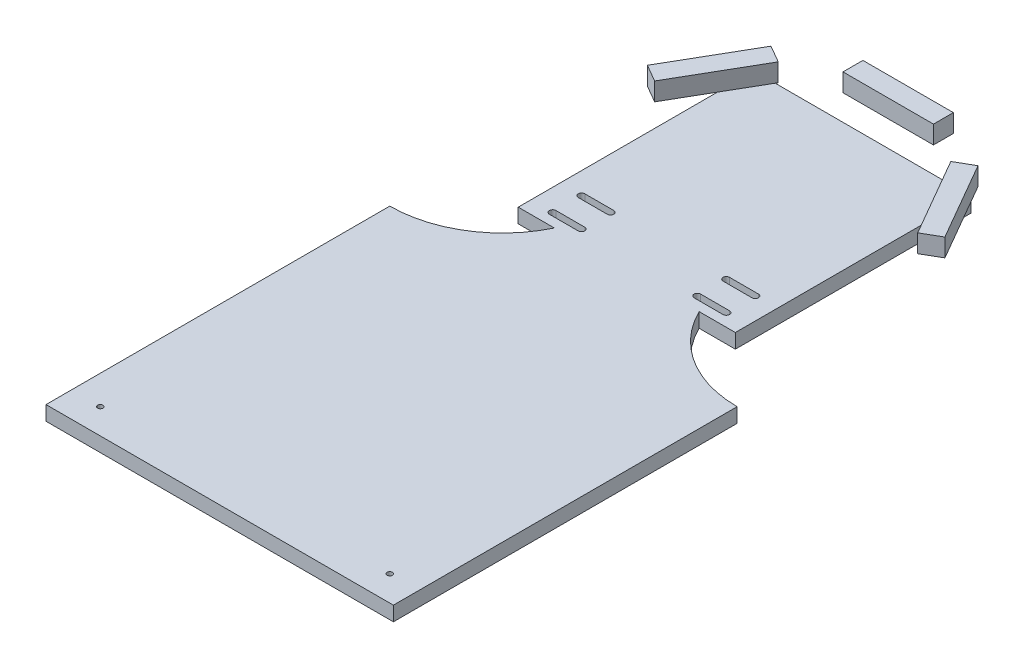
SolidWorks part; units mm, degrees
ref_plane "前视基准面" through (0, 0, 0) normal (0, 0, 1) x (1, 0, 0)
ref_plane "上视基准面" through (0, 0, 0) normal (0, 1, 0) x (1, 0, 0)
ref_plane "右视基准面" through (0, 0, 0) normal (1, 0, 0) x (0, 0, -1)
other "Configuration Table"
sketch "草图1" plane through (0, 0, 0) normal (0, 1, 0) x (1, 0, 0)
  line L1 (-60, 15) -> (60, 15) construction
  line L2 (-60, 15) -> (-60, -15)
  line L3 (-60, -15) -> (-40, -15)
  line L4 (60, 15) -> (60, -15)
  line L5 (-60, 15) -> (60, -15) construction
  line L6 (-60, -15) -> (60, 15) construction
  line L14 (-48, 8) -> (-32, 8) construction
  line L15 (-48, 9.8) -> (-32, 9.8)
  line L16 (-48, 6.2) -> (-32, 6.2)
  line L17 (-60, 0) -> (0, 0) construction
  line L18 (-48, -8) -> (-32, -8) construction
  line L19 (-48, -9.8) -> (-32, -9.8)
  line L20 (-48, -6.2) -> (-32, -6.2)
  line L21 (0, 15) -> (0, 0) construction
  line L22 (48, 8) -> (32, 8) construction
  line L23 (48, 9.8) -> (32, 9.8)
  line L24 (48, 6.2) -> (32, 6.2)
  line L25 (48, -8) -> (32, -8) construction
  line L26 (48, -9.8) -> (32, -9.8)
  line L27 (48, -6.2) -> (32, -6.2)
  line L28 (40, -15) -> (60, -15)
  line L31 (-40, -240) -> (40, -240)
  line L33 (40, -240) -> (96, -240)
  line L36 (-40, -240) -> (-96, -240)
  line L37 (-96, -50) -> (-96, -240)
  line L38 (96, -50) -> (96, -240)
  line L41 (60, 15) -> (-60, 15) construction
  line L42 (60, 15) -> (60, 115.3405)
  line L43 (60, 115.3405) -> (-60, 115.3405)
  line L44 (-60, 15) -> (-60, 115.3405)
  arc A4 (-48, 9.8) -> (-48, 6.2) centre (-48, 8) ccw
  arc A5 (-32, 6.2) -> (-32, 9.8) centre (-32, 8) ccw
  arc A6 (-48, -9.8) -> (-48, -6.2) centre (-48, -8) cw
  arc A7 (-32, -6.2) -> (-32, -9.8) centre (-32, -8) cw
  arc A8 (48, 9.8) -> (48, 6.2) centre (48, 8) cw
  arc A9 (32, 6.2) -> (32, 9.8) centre (32, 8) cw
  arc A10 (48, -9.8) -> (48, -6.2) centre (48, -8) ccw
  arc A11 (32, -6.2) -> (32, -9.8) centre (32, -8) ccw
  arc A12 (-96, -50) -> (-40, -15) centre (-96, 12.3) ccw
  arc A13 (96, -50) -> (40, -15) centre (96, 12.3) cw
  point P0 (0, 0)
  point P10 (40, 8)
  point P17 (40, -8)
  point P24 (-40, 8)
  point P33 (-40, -8)
  dimension "D5" = 8
  dimension "D1" = 30
  dimension "D2" = 120
  dimension "D3" = 3.6
  dimension "D4" = 16
  dimension "D6" = 40
  dimension "D8" = 80
  dimension "D9" = 240
  dimension "D11" = 190
extrude "凸台-拉伸1" add sketch "草图1" against normal blind 8
sketch "草图2" plane through (0, 0, 0) normal (0, 1, 0) x (1, 0, 0)
  line L0 (-82.215, -78.5994) -> (-57.215, -121.9006) construction
  line L1 (-96, -240) -> (96, -240) construction
  line L2 (0, -240) -> (0, -60) construction
  line L3 (-72.6888, -73.0994) -> (-47.6888, -116.4006) construction
  line L4 (-72.6888, -73.0994) -> (-82.215, -78.5994) construction
  line L5 (-25, -129.5) -> (25, -129.5) construction
  line L6 (-25, -129.5) -> (-25, -140.5) construction
  line L7 (-25, -140.5) -> (25, -140.5) construction
  line L8 (25, -129.5) -> (25, -140.5) construction
  line L9 (-25, -129.5) -> (25, -140.5) construction
  line L10 (-25, -140.5) -> (25, -129.5) construction
  line L11 (-47.6888, -116.4006) -> (-57.215, -121.9006) construction
  line L12 (47.6888, -116.4006) -> (72.6888, -73.0994) construction
  line L13 (47.6888, -116.4006) -> (57.215, -121.9006) construction
  line L14 (57.215, -121.9006) -> (82.215, -78.5994) construction
  line L15 (72.6888, -73.0994) -> (82.215, -78.5994) construction
  line L16 (-35.7665, 0) -> (35.7686, 0) construction
  line L17 (-25, 140.5) -> (25, 129.5) construction
  line L18 (-25, 129.5) -> (25, 140.5) construction
  line L19 (72.6888, 73.0994) -> (82.215, 78.5994)
  line L20 (57.215, 121.9006) -> (82.215, 78.5994)
  line L21 (47.6888, 116.4006) -> (57.215, 121.9006)
  line L22 (47.6888, 116.4006) -> (72.6888, 73.0994)
  line L23 (-47.6888, 116.4006) -> (-57.215, 121.9006)
  line L24 (25, 129.5) -> (25, 140.5)
  line L25 (-25, 140.5) -> (25, 140.5)
  line L26 (-25, 129.5) -> (-25, 140.5)
  line L27 (-25, 129.5) -> (25, 129.5)
  line L28 (-72.6888, 73.0994) -> (-82.215, 78.5994)
  line L29 (-72.6888, 73.0994) -> (-47.6888, 116.4006)
  line L30 (-82.215, 78.5994) -> (-57.215, 121.9006)
  circle A0 centre (0, -60) radius 75 construction
  point P5 (0, -135)
  point P33 (0, 135)
  dimension "D4" = 11
  dimension "D3" = 150
  dimension "D1" = 60
  dimension "D2" = 2
  dimension "D5" = 50
  dimension "D6" = 2
extrude "凸台-拉伸2" add sketch "草图2" along normal blind 10
sketch "草图4" plane through (0, 0, 0) normal (0, 1, 0) x (1, 0, 0)
  line L0 (0, 0) -> (0, -203.7521) construction
  circle A0 centre (-80, -226) radius 1.45
  circle A1 centre (80, -226) radius 1.45
  point P7 (-447.3861, 54.0255)
  point P8 (-142.8704, -129.9941)
  dimension "D1" = 2.9
  dimension "D2" = 80
  dimension "D3" = 226
extrude "切除-拉伸1" cut sketch "草图4" against normal through all
